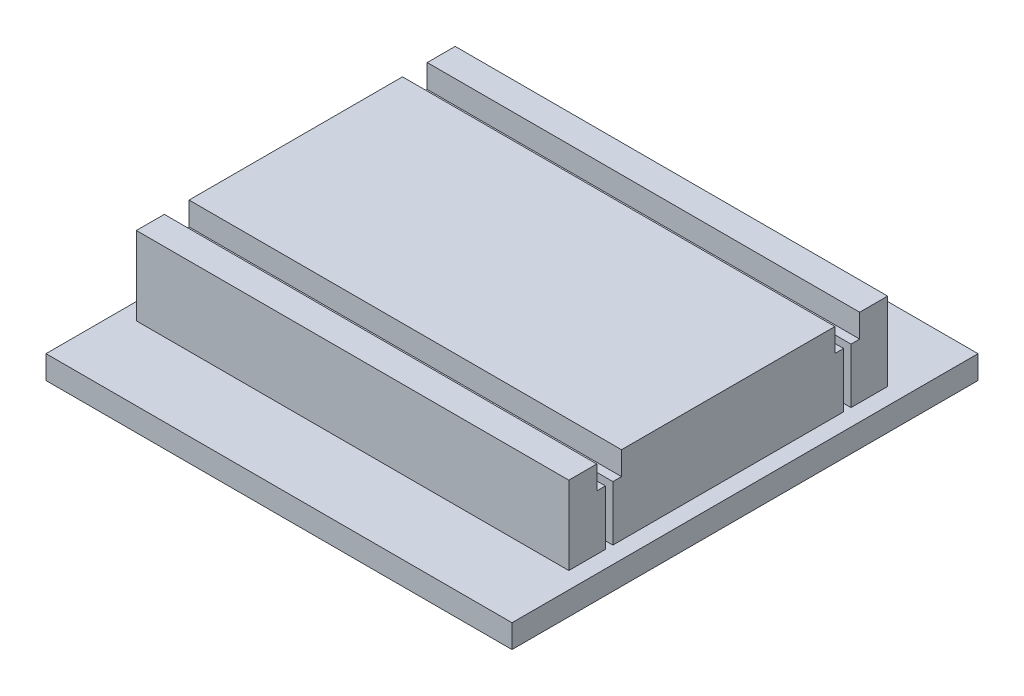
SolidWorks part; units mm, degrees
ref_plane "Front Plane" through (0, 0, 0) normal (0, 0, 1) x (1, 0, 0)
ref_plane "Top Plane" through (0, 0, 0) normal (0, 1, 0) x (1, 0, 0)
ref_plane "Right Plane" through (0, 0, 0) normal (1, 0, 0) x (0, 0, -1)
sketch "Sketch1" plane through (0, 0, 0) normal (0, 1, 0) x (1, 0, 0)
  line L1 (23.2, -12.375) -> (-23.2, -12.375)
  line L2 (23.2, -12.375) -> (23.2, 12.375)
  line L3 (23.2, 12.375) -> (-23.2, 12.375)
  line L4 (-23.2, -12.375) -> (-23.2, 12.375)
  line L5 (23.2, -12.375) -> (-23.2, 12.375) construction
  line L6 (23.2, 12.375) -> (-23.2, -12.375) construction
  point P0 (0, 0)
  dimension "D1" = 24.75
  dimension "D2" = 46.4
extrude "Boss-Extrude1" add sketch "Sketch1" along normal blind 5.9
sketch "Sketch2" plane through (0, 5.9, 0) normal (0, 1, 0) x (1, 0, 0)
  line L0 (23.2, 0) -> (23.2, 11.45)
  line L1 (23.2, -12.375) -> (23.2, 12.375) construction
  line L2 (23.2, 0) -> (23.2, -11.45)
  line L3 (23.2, -11.45) -> (23.2, 11.45)
  line L4 (23.2, -11.45) -> (-23.2, -11.45)
  line L5 (23.2, 11.45) -> (-23.2, 11.45)
  line L6 (-23.2, -11.45) -> (-23.2, 11.45)
  line M4 (-23.2, 12.375) -> (-23.2, -12.375)
  line M6 (23.2, -12.375) -> (23.2, 12.375)
  dimension "D1" = 11.45
  dimension "D2" = 11.45
  dimension "D3" = 46.4
extrude "Boss-Extrude2" add sketch "Sketch2" along normal blind 2.5 contours L5 L4 M6 M4
sketch "Sketch3" plane through (0, 0, 0) normal (0, -1, 0) x (1, 0, 0)
  line L1 (-25, 25) -> (25, 25)
  line L2 (-25, 25) -> (-25, -25)
  line L3 (-25, -25) -> (25, -25)
  line L4 (25, 25) -> (25, -25)
  line L5 (-25, 25) -> (25, -25) construction
  line L6 (-25, -25) -> (25, 25) construction
  point P0 (0, 0)
  dimension "D1" = 50
  dimension "D2" = 50
extrude "Boss-Extrude3" add sketch "Sketch3" along normal blind 2.5
sketch "Sketch4" plane through (0, 0, 0) normal (0, 1, 0) x (1, 0, 0)
  line L1 (-23.2, 12.375) -> (-23.2, 13.175)
  line L3 (23.2, 12.375) -> (23.2, 13.175)
  line L4 (23.2, 13.175) -> (-23.2, 13.175)
  line L5 (23.2, 13.175) -> (23.2, 15.175)
  line L6 (-23.2, 13.175) -> (-23.2, 15.175)
  line L7 (23.2, 15.175) -> (-23.2, 15.175)
  line L8 (23.2, 13.175) -> (-23.2, 13.175)
  line L9 (23.2, 13.175) -> (23.2, 14.105)
  line L10 (-23.2, 13.175) -> (-23.2, 14.105)
  line L11 (23.2, 14.105) -> (-23.2, 14.105)
  dimension "D1" = 0.8
  dimension "D2" = 2
  dimension "D3" = 0.93
extrude "Boss-Extrude4" add sketch "Sketch4" along normal up to surface (5.9 mm away) contours L5 L11 L6 L4 up to face at (0, 5.9, -11.9125)
sketch "Sketch5" plane through (0, 0, 0) normal (0, 1, 0) x (1, 0, 0)
  line L0 (-23.2, -12.375) -> (-23.2, -13.175)
  line L1 (23.2, -12.375) -> (23.2, -13.175)
  line L2 (23.2, -13.175) -> (-23.2, -13.175)
  line L3 (23.2, -13.175) -> (23.2, -14.105)
  line L4 (-23.2, -13.175) -> (-23.2, -14.105)
  line L5 (23.2, -14.105) -> (-23.2, -14.105)
  dimension "D1" = 0.8
  dimension "D2" = 0.93
extrude "Boss-Extrude5" add sketch "Sketch5" along normal up to surface (5.9 mm away) contours L5 L3 L2 L4 up to face at (0, 5.9, 11.9125)
sketch "Sketch6" plane through (0, 0, 0) normal (0, 1, 0) x (1, 0, 0)
  line L0 (-23.2, 14.105) -> (23.2, 14.105)
  line L1 (-23.2, 14.105) -> (-23.2, 17.105)
  line L2 (23.2, 14.105) -> (23.2, 17.105)
  line L3 (-23.2, 17.105) -> (23.2, 17.105)
  dimension "D1" = 3
extrude "Boss-Extrude6" add sketch "Sketch6" along normal up to surface (8.4 mm away) up to face at (0, 8.4, 0)
sketch "Sketch7" plane through (0, 0, 0) normal (0, 1, 0) x (1, 0, 0)
  line L0 (23.2, -14.105) -> (-23.2, -14.105)
  line L1 (23.2, -14.105) -> (23.2, -17.105)
  line L2 (-23.2, -14.105) -> (-23.2, -17.105)
  line L3 (23.2, -17.105) -> (-23.2, -17.105)
  dimension "D1" = 3
extrude "Boss-Extrude7" add sketch "Sketch7" along normal up to surface (8.4 mm away) up to face at (0, 8.4, 0)
